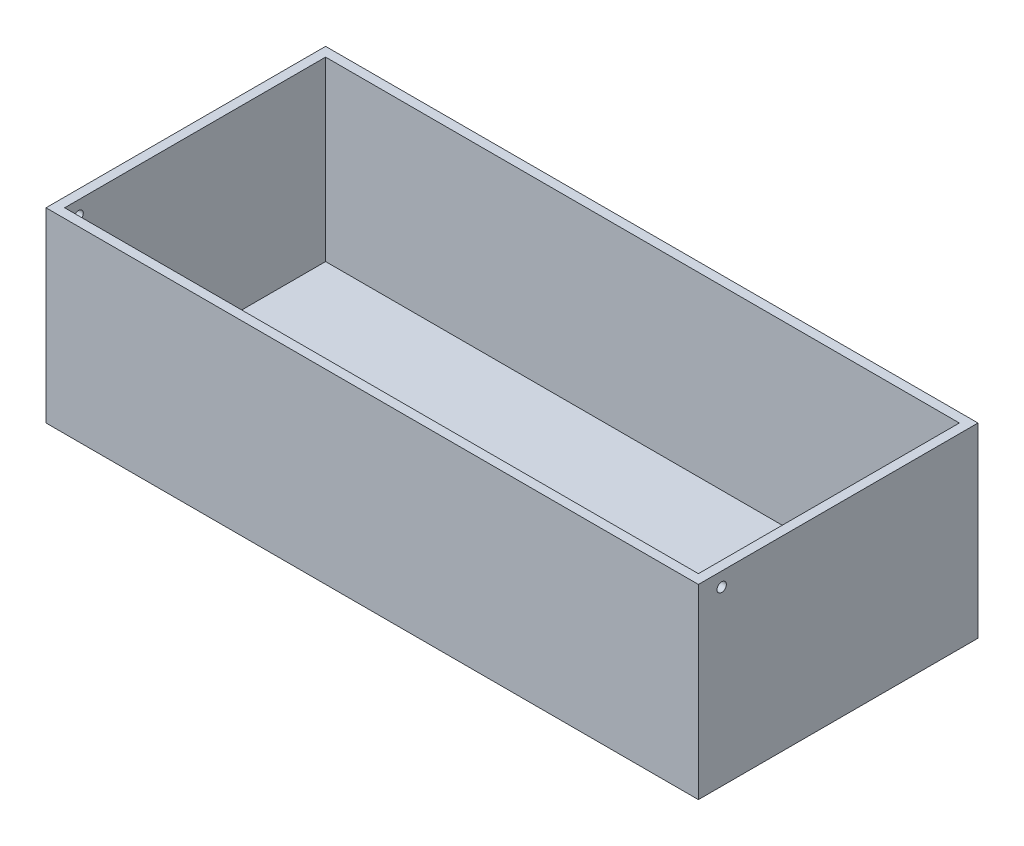
SolidWorks part; units mm, degrees
ref_plane "Alzado" through (0, 0, 0) normal (0, 0, 1) x (1, 0, 0)
ref_plane "Planta" through (0, 0, 0) normal (0, 1, 0) x (1, 0, 0)
ref_plane "Vista lateral" through (0, 0, 0) normal (1, 0, 0) x (0, 0, -1)
sketch "Croquis1" plane through (0, 0, 0) normal (0, 1, 0) x (1, 0, 0)
  line L1 (-350, -150) -> (350, -150)
  line L2 (-350, -150) -> (-350, 150)
  line L3 (-350, 150) -> (350, 150)
  line L4 (350, -150) -> (350, 150)
  line L5 (-350, -150) -> (350, 150) construction
  line L6 (-350, 150) -> (350, -150) construction
  point P1 (0, 0)
  dimension "D1" = 700
  dimension "D2" = 300
extrude "Saliente-Extruir1" add sketch "Croquis1" along normal blind 200
sketch "Croquis2" plane through (0, 200, 0) normal (0, 1, 0) x (1, 0, 0)
  line L1 (-340, -140) -> (340, -140)
  line L2 (-340, -140) -> (-340, 140)
  line L3 (-340, 140) -> (340, 140)
  line L4 (340, -140) -> (340, 140)
  line L5 (-340, -140) -> (340, 140) construction
  line L6 (-340, 140) -> (340, -140) construction
  point P0 (0, 0)
  dimension "D1" = 680
  dimension "D2" = 280
extrude "Cortar-Extruir1" cut sketch "Croquis2" against normal blind 190
sketch "Croquis3" plane through (350, 0, 0) normal (1, 0, 0) x (0, 0, -1)
  line L0 (-150, 200) -> (150, 200) construction
  line L1 (-150, 200) -> (-150, 0) construction
  circle A0 centre (-125, 185) radius 5
  dimension "D1" = 15
  dimension "D2" = 25
extrude "Cortar-Extruir2" cut sketch "Croquis3" against normal blind 700
